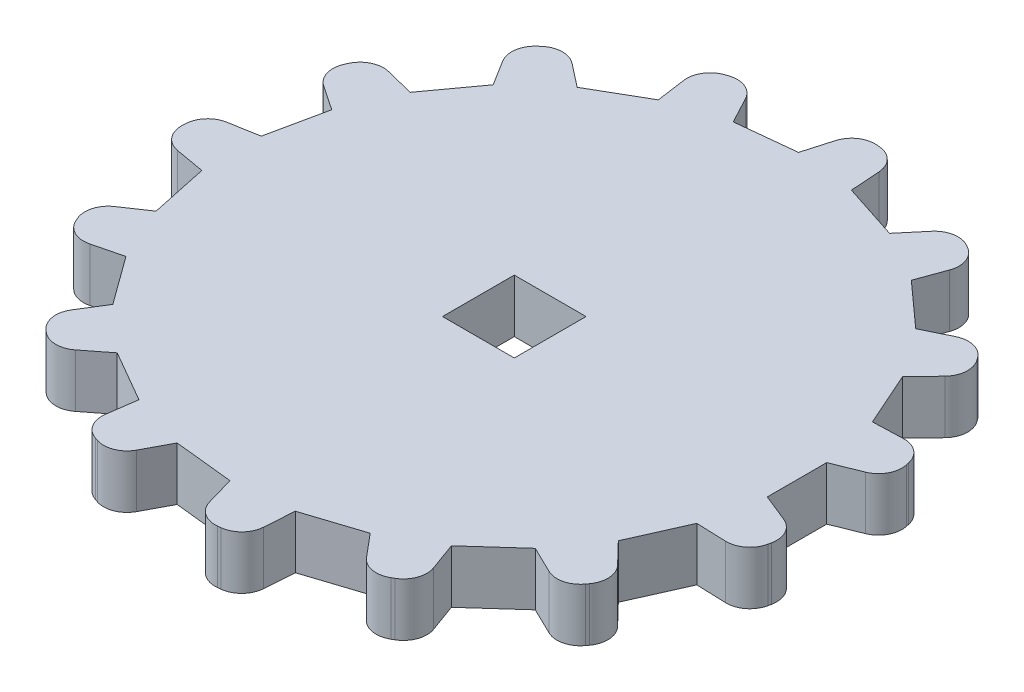
SolidWorks part; units mm, degrees
ref_plane "Front Plane" through (0, 0, 0) normal (0, 0, 1) x (1, 0, 0)
ref_plane "Top Plane" through (0, 0, 0) normal (0, 1, 0) x (1, 0, 0)
ref_plane "Right Plane" through (0, 0, 0) normal (1, 0, 0) x (0, 0, -1)
sketch "Sketch1" plane through (0, 0, 0) normal (0, 1, 0) x (1, 0, 0)
  line L0 (0, 0) -> (0, 101.6)
  line L1 (0, 0) -> (21.1238, 99.3798)
  line L2 (0, 0) -> (41.3244, 92.8162)
  line L3 (0, 101.6) -> (2.9417, 111.8588)
  line L4 (11.8751, 117.8844) -> (12.8939, 117.7774)
  line L5 (20.3794, 110.026) -> (21.1238, 99.3798)
  line L6 (41.3244, 92.8162) -> (21.1238, 99.3798)
  line L7 (58.7964, 102.8628) -> (59.6836, 102.3505)
  line L8 (63.3691, 92.2247) -> (59.719, 82.1961)
  line L9 (41.3244, 92.8162) -> (48.1844, 100.9916)
  line L10 (75.5035, 67.9837) -> (59.719, 82.1961)
  line L11 (95.5512, 70.0552) -> (96.1534, 69.2264)
  line L12 (95.4017, 58.4769) -> (87.9882, 50.8)
  line L13 (75.5035, 67.9837) -> (85.0956, 72.662)
  line L14 (96.6273, 31.3961) -> (87.9882, 50.8)
  line L15 (115.7844, 25.1344) -> (115.9974, 24.1323)
  line L16 (110.9385, 14.618) -> (101.0434, 10.6201)
  line L17 (96.6273, 31.3961) -> (107.293, 31.7686)
  line L18 (101.0434, -10.6201) -> (101.0434, 10.6201)
  line L19 (115.9974, -24.1323) -> (115.7844, -25.1344)
  line L20 (107.293, -31.7686) -> (96.6273, -31.3961)
  line L21 (101.0434, -10.6201) -> (110.9385, -14.618)
  line L22 (87.9882, -50.8) -> (96.6273, -31.3961)
  line L23 (96.1534, -69.2264) -> (95.5512, -70.0552)
  line L24 (85.0956, -72.662) -> (75.5035, -67.9837)
  line L25 (87.9882, -50.8) -> (95.4017, -58.4769)
  line L26 (59.719, -82.1961) -> (75.5035, -67.9837)
  line L27 (59.6836, -102.3505) -> (58.7964, -102.8628)
  line L28 (48.1844, -100.9916) -> (41.3244, -92.8162)
  line L29 (59.719, -82.1961) -> (63.3691, -92.2247)
  line L30 (21.1238, -99.3798) -> (41.3244, -92.8162)
  line L31 (12.8939, -117.7774) -> (11.8751, -117.8844)
  line L32 (2.9417, -111.8588) -> (0, -101.6)
  line L33 (21.1238, -99.3798) -> (20.3794, -110.026)
  line L34 (-21.1238, -99.3798) -> (0, -101.6)
  line L35 (-36.1252, -112.8394) -> (-37.0995, -112.5228)
  line L36 (-42.8097, -103.3845) -> (-41.3244, -92.8162)
  line L37 (-21.1238, -99.3798) -> (-26.1341, -108.8028)
  line L38 (-59.719, -82.1961) -> (-41.3244, -92.8162)
  line L39 (-78.8979, -88.3905) -> (-79.6592, -87.705)
  line L40 (-81.1589, -77.0342) -> (-75.5035, -67.9837)
  line L41 (-59.719, -82.1961) -> (-68.1288, -88.7666)
  line L42 (-87.9882, -50.8) -> (-75.5035, -67.9837)
  line L43 (-108.0285, -48.6581) -> (-108.4452, -47.7222)
  line L44 (-105.475, -37.3639) -> (-96.6273, -31.3961)
  line L45 (-87.9882, -50.8) -> (-98.3434, -53.3818)
  line L46 (-101.0434, -10.6201) -> (-96.6273, -31.3961)
  line L47 (-118.48, -0.5122) -> (-118.48, 0.5122)
  line L48 (-111.5535, 8.7669) -> (-101.0434, 10.6201)
  line L49 (-101.0434, -10.6201) -> (-111.5535, -8.7669)
  line L50 (-96.6273, 31.3961) -> (-101.0434, 10.6201)
  line L51 (-108.4452, 47.7222) -> (-108.0285, 48.6581)
  line L52 (-98.3434, 53.3818) -> (-87.9882, 50.8)
  line L53 (-96.6273, 31.3961) -> (-105.475, 37.3639)
  line L54 (-75.5035, 67.9837) -> (-87.9882, 50.8)
  line L55 (-79.6592, 87.705) -> (-78.8979, 88.3905)
  line L56 (-68.1288, 88.7666) -> (-59.719, 82.1961)
  line L57 (-75.5035, 67.9837) -> (-81.1589, 77.0342)
  line L58 (-41.3244, 92.8162) -> (-59.719, 82.1961)
  line L59 (-37.0995, 112.5228) -> (-36.1252, 112.8394)
  line L60 (-26.1341, 108.8028) -> (-21.1238, 99.3798)
  line L61 (-41.3244, 92.8162) -> (-42.8097, 103.3845)
  line L62 (0, 101.6) -> (-21.1238, 99.3798)
  arc A1 (12.8939, 117.7774) -> (20.3794, 110.026) centre (12.0178, 109.4413) cw
  arc A2 (11.8751, 117.8844) -> (2.9417, 111.8588) centre (10.9989, 109.5484) ccw
  arc A3 (58.7964, 102.8628) -> (48.1844, 100.9916) centre (54.6054, 95.6037) ccw
  arc A4 (59.6836, 102.3505) -> (63.3691, 92.2247) centre (55.4926, 95.0915) cw
  arc A5 (95.5512, 70.0552) -> (85.0956, 72.662) centre (88.77, 65.1284) ccw
  arc A6 (96.1534, 69.2264) -> (95.4017, 58.4769) centre (89.3722, 64.2996) cw
  arc A7 (115.7844, 25.1344) -> (107.293, 31.7686) centre (107.5855, 23.3917) ccw
  arc A8 (115.9974, 24.1323) -> (110.9385, 14.618) centre (107.7985, 22.3896) cw
  arc A9 (115.9974, -24.1323) -> (110.9385, -14.618) centre (107.7985, -22.3896) ccw
  arc A10 (115.7844, -25.1344) -> (107.293, -31.7686) centre (107.5855, -23.3917) cw
  arc A11 (96.1534, -69.2264) -> (95.4017, -58.4769) centre (89.3722, -64.2996) ccw
  arc A12 (95.5512, -70.0552) -> (85.0956, -72.662) centre (88.77, -65.1284) cw
  arc A13 (59.6836, -102.3505) -> (63.3691, -92.2247) centre (55.4926, -95.0915) ccw
  arc A14 (58.7964, -102.8628) -> (48.1844, -100.9916) centre (54.6054, -95.6037) cw
  arc A15 (12.8939, -117.7774) -> (20.3794, -110.026) centre (12.0178, -109.4413) ccw
  arc A16 (11.8751, -117.8844) -> (2.9417, -111.8588) centre (10.9989, -109.5484) cw
  arc A17 (-36.1252, -112.8394) -> (-26.1341, -108.8028) centre (-33.535, -104.8677) ccw
  arc A18 (-37.0995, -112.5228) -> (-42.8097, -103.3845) centre (-34.5093, -104.5511) cw
  arc A19 (-78.8979, -88.3905) -> (-68.1288, -88.7666) centre (-73.2892, -82.1615) ccw
  arc A20 (-79.6592, -87.705) -> (-81.1589, -77.0342) centre (-74.0506, -81.476) cw
  arc A21 (-108.0285, -48.6581) -> (-98.3434, -53.3818) centre (-100.3711, -45.2488) ccw
  arc A22 (-108.4452, -47.7222) -> (-105.475, -37.3639) centre (-100.7878, -44.3129) cw
  arc A23 (-118.48, -0.5122) -> (-111.5535, -8.7669) centre (-110.098, -0.5122) ccw
  arc A24 (-118.48, 0.5122) -> (-111.5535, 8.7669) centre (-110.098, 0.5122) cw
  arc A25 (-108.4452, 47.7222) -> (-105.475, 37.3639) centre (-100.7878, 44.3129) ccw
  arc A26 (-108.0285, 48.6581) -> (-98.3434, 53.3818) centre (-100.3711, 45.2488) cw
  arc A27 (-79.6592, 87.705) -> (-81.1589, 77.0342) centre (-74.0506, 81.476) ccw
  arc A28 (-78.8979, 88.3905) -> (-68.1288, 88.7666) centre (-73.2892, 82.1615) cw
  arc A29 (-37.0995, 112.5228) -> (-42.8097, 103.3845) centre (-34.5093, 104.5511) ccw
  arc A30 (-36.1252, 112.8394) -> (-26.1341, 108.8028) centre (-33.535, 104.8677) cw
  point P140 (0, 0)
  dimension "D7" = 8.382
  dimension "D2" = 12
  dimension "D3" = 12
  dimension "D4" = 84
  dimension "D5" = 80
  dimension "D6" = 80
  dimension "D8" = 15
extrude "Boss-Extrude1" add sketch "Sketch1" along normal blind 19.05 contours L4 A2 L3 L0 L1 L5 A1 | L2 L6 L1 | A30 L59 A29 L61 L58 L56 A28 L55 A27 L57 L54 L52 A26 L51 A25 L53 L50 L48 A24 L47 A23 L49 L46 L44 A22 L43 A21 L45 L42 L40 A20 L39 A19 L41 L38 L36 A18 L35 A17 L37 L34 L32 A16 L31 A15 L33 L30 L28 A14 L27 A13
sketch "Sketch2" plane through (0, 19.05, 0) normal (0, 1, 0) x (1, 0, 0)
  circle A0 centre (0, 0) radius 3.175
extrude "Cut-Extrude1" cut sketch "Sketch2" against normal through all
sketch "Sketch4" plane through (0, 19.05, 0) normal (0, 1, 0) x (1, 0, 0)
  line L1 (-12.827, 12.827) -> (12.827, 12.827)
  line L2 (-12.827, 12.827) -> (-12.827, -12.827)
  line L3 (-12.827, -12.827) -> (12.827, -12.827)
  line L4 (12.827, 12.827) -> (12.827, -12.827)
  line L5 (-12.827, 12.827) -> (12.827, -12.827) construction
  line L6 (-12.827, -12.827) -> (12.827, 12.827) construction
  point P0 (0, 0)
  dimension "D1" = 25.654
  dimension "D2" = 25.654
extrude "Cut-Extrude2" cut sketch "Sketch4" against normal through all
